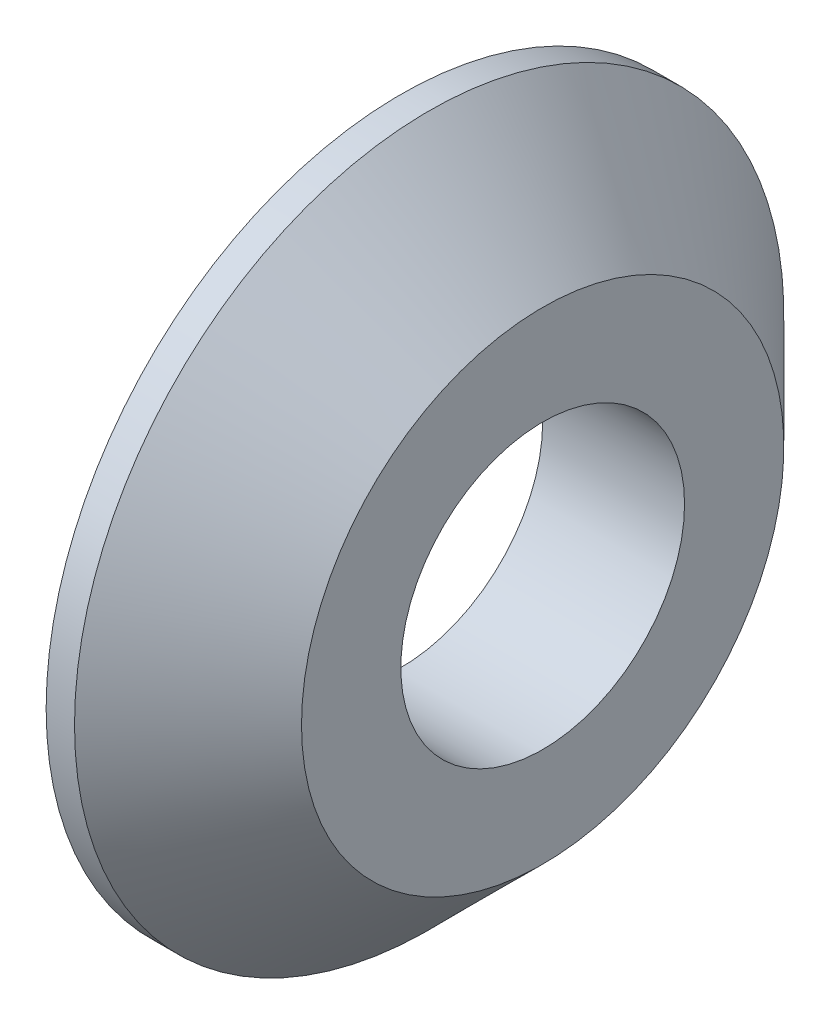
SolidWorks part; units mm, degrees
ref_plane "Front Plane" through (0, 0, 0) normal (0, 0, 1) x (1, 0, 0)
ref_plane "Top Plane" through (0, 0, 0) normal (0, 1, 0) x (1, 0, 0)
ref_plane "Right Plane" through (0, 0, 0) normal (1, 0, 0) x (0, 0, -1)
sketch "Croquis1" plane through (0, 0, 0) normal (0, 0, 1) x (1, 0, 0)
  line L0 (0, 0) -> (0, 2.5)
  line L1 (0, 2.5) -> (0.2, 2.5)
  line L2 (1, 0) -> (1, 1.7)
  line L3 (1, 1.7) -> (0.2, 2.5)
  line L4 (0, 0) -> (1, 0)
  dimension "D1" = 1
  dimension "D2" = 2.5
  dimension "D3" = 1.7
  dimension "D4" = 0.2
revolve "Revolución1" add sketch "Croquis1" angle 360 about L4
sketch "Croquis2" plane through (1, 0, 0) normal (1, 0, 0) x (0, 0, -1)
  circle A0 centre (0, 0) radius 1
  dimension "D1" = 2
extrude "Cortar-Extruir1" cut sketch "Croquis2" against normal through all
